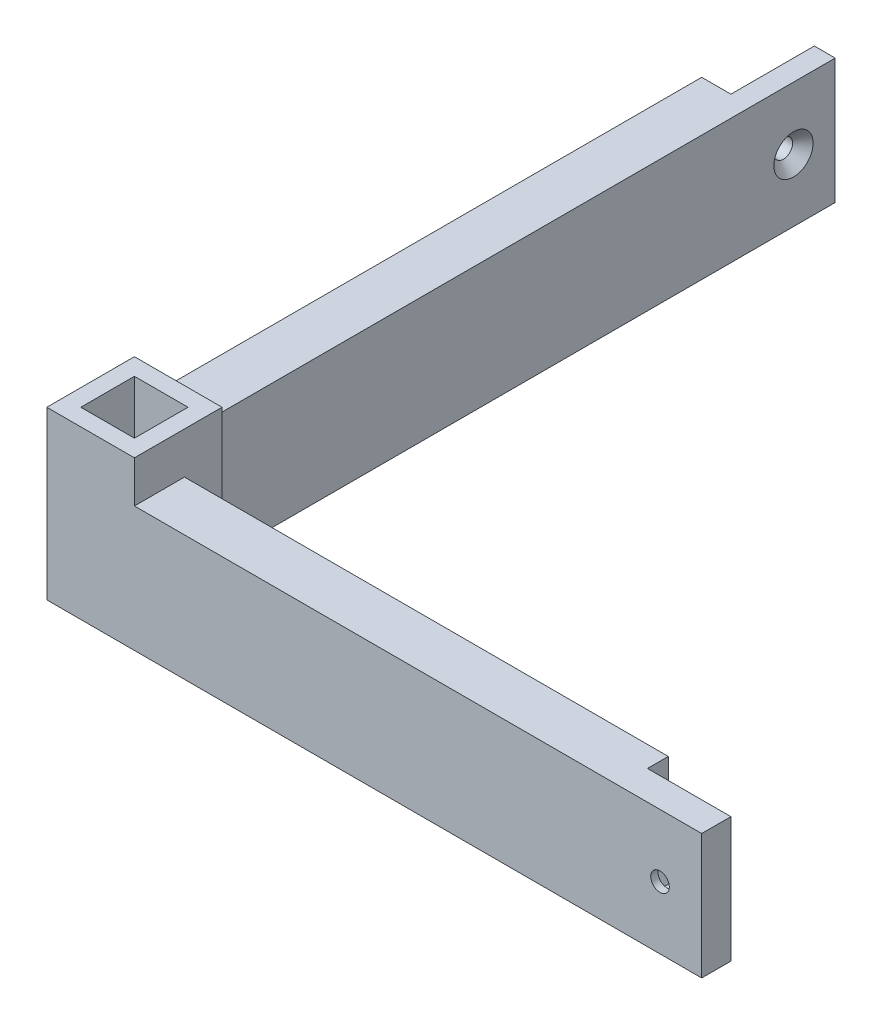
SolidWorks part; units mm, degrees
ref_plane "Front Plane" through (0, 0, 0) normal (0, 0, 1) x (1, 0, 0)
ref_plane "Top Plane" through (0, 0, 0) normal (0, 1, 0) x (1, 0, 0)
ref_plane "Right Plane" through (0, 0, 0) normal (1, 0, 0) x (0, 0, -1)
sketch "Sketch1" plane through (0, 0, 0) normal (1, 0, 0) x (0, 0, -1)
  line L1 (-7.6487, 23.9945) -> (13.3513, 23.9945)
  line L2 (-7.6487, 23.9945) -> (-7.6487, -16.0055)
  line L3 (-7.6487, -16.0055) -> (13.3513, -16.0055)
  line L4 (13.3513, 23.9945) -> (13.3513, -16.0055)
  line L5 (2.8513, -16.0055) -> (2.8513, 23.9945) construction
  line L6 (-7.6487, 3.9945) -> (13.3513, 3.9945) construction
  point P352 (2.8513, 3.9945)
  dimension "D1" = 40
  dimension "D2" = 21
extrude "Boss-Extrude1" add sketch "Sketch1" along normal blind 21
sketch "Sketch7" plane through (0, 0, -13.3513) normal (0, 0, -1) x (-1, 0, 0)
  line L1 (0, -16.0055) -> (-12, -16.0055)
  line L2 (0, -16.0055) -> (0, 13.9945)
  line L3 (0, 13.9945) -> (-12, 13.9945)
  line L4 (-12, -16.0055) -> (-12, 13.9945)
  line L5 (-6, 13.9945) -> (-6, -16.0055) construction
  line L6 (0, -1.0055) -> (-12, -1.0055) construction
  point P268 (-6, -1.0055)
  dimension "D1" = 12
  dimension "D2" = 30
sketch "Sketch8" plane through (0, 23.9945, 0) normal (0, 1, 0) x (1, 0, 0)
  line L0 (21, 13.3513) -> (21, -7.6487) construction
  line L1 (4.075, -3.5737) -> (16.925, -3.5737)
  line L2 (4.075, -3.5737) -> (4.075, 9.2763)
  line L3 (4.075, 9.2763) -> (16.925, 9.2763)
  line L4 (16.925, -3.5737) -> (16.925, 9.2763)
  line L5 (4.075, -3.5737) -> (16.925, 9.2763) construction
  line L6 (4.075, 9.2763) -> (16.925, -3.5737) construction
  line L7 (10.5, -3.5737) -> (10.5, -7.6487) construction
  line L9 (21, -7.6487) -> (0, -7.6487) construction
  line L10 (16.925, 2.8513) -> (21, 2.8513) construction
  line L11 (10.5, 9.2763) -> (10.5, 13.3513) construction
  line L12 (0, 13.3513) -> (12, 13.3513) construction
  point P0 (10.5, 2.8513)
  dimension "D1" = 12.85
  dimension "D2" = 12.85
extrude "Cut-Extrude2" cut sketch "Sketch8" against normal blind 40
extrude "Boss-Extrude5" add sketch "Sketch7" along normal blind 156
sketch "Sketch9" plane through (21, 0, 0) normal (1, 0, 0) x (0, 0, -1)
  line L1 (-7.6487, -16.0055) -> (4.3513, -16.0055)
  line L2 (-7.6487, -16.0055) -> (-7.6487, 13.9945)
  line L3 (-7.6487, 13.9945) -> (4.3513, 13.9945)
  line L4 (4.3513, -16.0055) -> (4.3513, 13.9945)
  line L5 (-1.6487, 13.9945) -> (-1.6487, -16.0055) construction
  line L6 (-7.6487, -1.0055) -> (4.3513, -1.0055) construction
  point P124 (-1.6487, -1.0055)
  dimension "D1" = 12
  dimension "D2" = 30
extrude "Boss-Extrude6" add sketch "Sketch9" along normal blind 116
sketch "Sketch10" plane through (137, 0, 0) normal (1, 0, 0) x (0, 0, -1)
  line L0 (4.3513, 13.9945) -> (-7.6487, 13.9945) construction
  line L1 (-1.6487, 13.9945) -> (-7.6487, 13.9945)
  line L2 (-1.6487, 13.9945) -> (-1.6487, -16.0055)
  line L3 (-1.6487, -16.0055) -> (-7.6487, -16.0055)
  line L4 (-7.6487, 13.9945) -> (-7.6487, -16.0055)
  line L5 (-4.6487, -16.0055) -> (-4.6487, 13.9945) construction
  line L6 (-1.6487, -1.0055) -> (-7.6487, -1.0055) construction
  point P196 (-4.6487, -1.0055)
extrude "Boss-Extrude7" add sketch "Sketch10" along normal blind 20
sketch "Sketch11" plane through (0, 0, -169.3513) normal (0, 0, -1) x (-1, 0, 0)
  line L1 (-7, 13.9945) -> (0, 13.9945)
  line L2 (-7, 13.9945) -> (-7, -16.0055)
  line L3 (-7, -16.0055) -> (0, -16.0055)
  line L4 (0, 13.9945) -> (0, -16.0055)
  line L5 (-3.5, -16.0055) -> (-3.5, 13.9945) construction
  line L6 (-7, -1.0055) -> (0, -1.0055) construction
  line L7 (-12, 13.9945) -> (-12, -16.0055) construction
  point P6 (-24.9651, -5.4081)
  point P348 (-3.5, -1.0055)
  dimension "D1" = 7
extrude "Cut-Extrude3" cut sketch "Sketch11" against normal blind 20
sketch "Sketch12" plane through (7, 0, 0) normal (-1, 0, 0) x (0, 0, 1)
  line L0 (-159.3513, 13.9945) -> (-159.3513, 2.5945) construction
  line L1 (-161.4298, 2.5945) -> (-163.5082, -1.0055)
  line L2 (-163.5082, -1.0055) -> (-161.4298, -4.6055)
  line L3 (-161.4298, -4.6055) -> (-157.2729, -4.6055)
  line L4 (-157.2729, -4.6055) -> (-155.1944, -1.0055)
  line L5 (-155.1944, -1.0055) -> (-157.2729, 2.5945)
  line L6 (-157.2729, 2.5945) -> (-161.4298, 2.5945)
  line L7 (-159.3513, -4.6055) -> (-159.3513, -16.0055) construction
  line L8 (-149.3513, -16.0055) -> (-169.3513, -16.0055) construction
  line L9 (-149.3513, 13.9945) -> (-169.3513, 13.9945) construction
  line L10 (-163.5082, -1.0055) -> (-169.3513, -1.0055) construction
  line L11 (-169.3513, 13.9945) -> (-169.3513, -16.0055) construction
  line L12 (-159.3513, 2.5945) -> (-159.3513, -4.6055) construction
  circle A0 centre (-159.3513, -1.0055) radius 3.6 construction
  circle A1 centre (-159.3513, -1.0055) radius 2.1
  dimension "D2" = 7.2
sketch "Sketch13" plane through (12, 0, 0) normal (-1, 0, 0) x (0, 0, 1)
  circle A0 centre (-159.3513, -1.0055) radius 2.1
  circle A1 centre (-159.3513, -1.0055) radius 2.1 construction
  point P0 (-159.3513, -1.0055)
sketch "Sketch16" plane through (0, 0, 1.6487) normal (0, 0, -1) x (-1, 0, 0)
  line L0 (-147, 2.5695) -> (-147, -4.5805) construction
  line L1 (-149.064, 2.5695) -> (-151.1281, -1.0055)
  line L2 (-151.1281, -1.0055) -> (-149.064, -4.5805)
  line L3 (-149.064, -4.5805) -> (-144.936, -4.5805)
  line L4 (-144.936, -4.5805) -> (-142.8719, -1.0055)
  line L5 (-142.8719, -1.0055) -> (-144.936, 2.5695)
  line L6 (-144.936, 2.5695) -> (-149.064, 2.5695)
  line L7 (-147, -16.0055) -> (-147, -4.5805) construction
  line L8 (-157, -16.0055) -> (-137, -16.0055) construction
  line L9 (-151.1281, -1.0055) -> (-157, -1.0055) construction
  line L10 (-157, -16.0055) -> (-157, 13.9945) construction
  line L11 (-147, 2.5695) -> (-147, 13.9945) construction
  line L12 (-157, 13.9945) -> (-137, 13.9945) construction
  circle A0 centre (-147, -1.0055) radius 4.1281 construction
  dimension "D1" = 7.15
extrude "Cut-Extrude7" cut sketch "Sketch16" against normal blind 4.25
hole_wizard "CSK for M4 Countersunk Flat Head Screw1" positions "Sketch13" profile "Sketch19" countersink size "M4" standard "DIN"
sketch "Sketch19" plane through (12, -1.0055, -159.3513) normal (0, 1, 0) x (0, 0, -1)
  line L0 (0, 0) -> (0, 17.3519)
  line L1 (0, 17.3519) -> (2.25, 16)
  line L2 (2.25, 16) -> (2.25, 2.45)
  line L3 (2.25, 2.45) -> (4.7, 0)
  line L5 (4.7, 0) -> (0, 0)
  line L6 (-2.25, 2.45) -> (-4.7, 0) construction
  line L10 (0, 17.3519) -> (-2.25, 16) construction
  line L11 (0, -6.35) -> (0, 107.95) construction
  dimension "Hole Dia." = 4.5
  dimension "Hole Depth" = 16
  dimension "Near C'Sink Dia." = 9.4
  dimension "Near C'Sink Angle" = 90
  dimension "Drill Angle" = 118
sketch "Sketch20" plane through (0, 0, 1.6487) normal (0, 0, -1) x (-1, 0, 0)
  line L1 (-144.936, -4.5805) -> (-142.8719, -1.0055)
  line L2 (-142.8719, -1.0055) -> (-144.936, 2.5695)
  line L3 (-144.936, 2.5695) -> (-149.064, 2.5695)
  line L4 (-149.064, 2.5695) -> (-151.1281, -1.0055)
  line L5 (-151.1281, -1.0055) -> (-149.064, -4.5805)
  line L6 (-149.064, -4.5805) -> (-144.936, -4.5805)
  circle A0 centre (-147, -1.0055) radius 3.575 construction
sketch "Sketch26" plane through (0, 0, 1.6487) normal (0, 0, -1) x (-1, 0, 0)
  line L7 (-149.064, 2.5695) -> (-151.1281, -1.0055)
  line L8 (-151.1281, -1.0055) -> (-149.064, -4.5805)
  line L9 (-149.064, -4.5805) -> (-144.936, -4.5805)
  line L10 (-144.936, -4.5805) -> (-142.8719, -1.0055)
  line L11 (-142.8719, -1.0055) -> (-144.936, 2.5695)
  line L12 (-144.936, 2.5695) -> (-149.064, 2.5695)
  circle A0 centre (-147, -1.0055) radius 4.1281 construction
sketch "Sketch24" plane through (0, -16.0055, 0) normal (0, -1, 0) x (-1, 0, 0)
  line L0 (-21, 13.3513) -> (-30, 4.3513)
  line L1 (-137, 4.3513) -> (-21, 4.3513) construction
  line L2 (-30, 4.3513) -> (-21, 4.3513)
  line L3 (-21, 4.3513) -> (-21, 13.3513)
extrude "Boss-Extrude10" add sketch "Sketch24" against normal blind 8
sketch "Sketch25" plane through (0, -16.0055, 0) normal (0, -1, 0) x (-1, 0, 0)
  line L0 (-21, 13.3513) -> (-12, 22.3513)
  line L1 (-12, 169.3513) -> (-12, 13.3513) construction
  line L2 (-12, 22.3513) -> (-12, 13.3513)
  line L3 (-12, 13.3513) -> (-21, 13.3513)
extrude "Boss-Extrude11" add sketch "Sketch25" against normal blind 8
sketch "Sketch27" plane through (0, 0, 1.6487) normal (0, 0, -1) x (-1, 0, 0)
  line L1 (-157, 13.9945) -> (-137, 13.9945)
  line L2 (-157, 13.9945) -> (-157, -16.0055)
  line L3 (-157, -16.0055) -> (-137, -16.0055)
  line L4 (-137, 13.9945) -> (-137, -16.0055)
  line L5 (-147, -16.0055) -> (-147, 13.9945) construction
  line L6 (-157, -1.0055) -> (-137, -1.0055) construction
  point P508 (-147, -1.0055)
extrude "Boss-Extrude12" add sketch "Sketch27" along normal blind 1
sketch "Sketch18" plane through (0, 0, 0.6487) normal (0, 0, -1) x (-1, 0, 0)
  line L0 (-147, 13.9945) -> (-147, -1.0055) construction
  line L2 (-147, -1.0055) -> (-147, -16.0055) construction
  line L4 (-151.1281, -1.0055) -> (-147, -1.0055) construction
  line L5 (-137, 13.9945) -> (-157, 13.9945) construction
  circle A0 centre (-147, -1.0055) radius 2.2269
  point P5 (-147, 13.9945)
  point P6 (0, 0)
  point P9 (-147, 13.9945)
extrude "Cut-Extrude10" cut sketch "Sketch18" against normal blind 10.4 from surface at 0 starting at face at (147, -1.0055, 0.6487)
